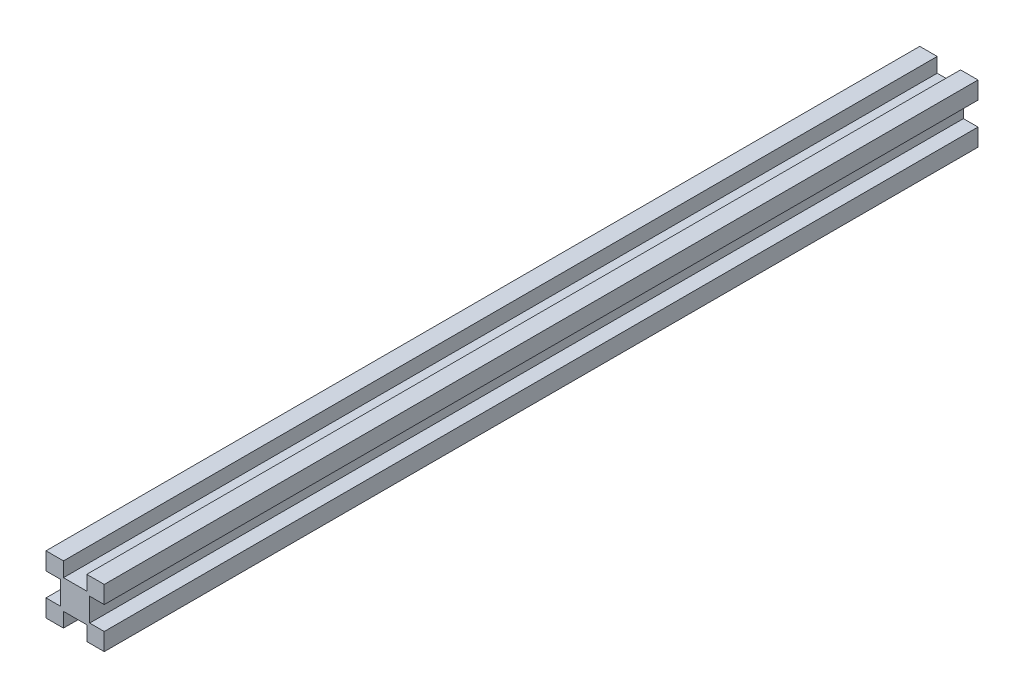
SolidWorks part; units mm, degrees
ref_plane "Alzado" through (0, 0, 0) normal (0, 0, 1) x (1, 0, 0)
ref_plane "Planta" through (0, 0, 0) normal (0, 1, 0) x (1, 0, 0)
ref_plane "Vista lateral" through (0, 0, 0) normal (1, 0, 0) x (0, 0, -1)
sketch "Croquis1" plane through (0, 0, 0) normal (0, 0, 1) x (1, 0, 0)
  line L1 (-23.5326, 14.5417) -> (-3.5326, 14.5417)
  line L2 (-23.5326, 14.5417) -> (-23.5326, -5.4583)
  line L3 (-23.5326, -5.4583) -> (-3.5326, -5.4583)
  line L4 (-3.5326, 14.5417) -> (-3.5326, -5.4583)
  line L5 (-23.5326, 14.5417) -> (-3.5326, -5.4583) construction
  line L6 (-23.5326, -5.4583) -> (-3.5326, 14.5417) construction
  point P0 (-13.5326, 4.5417)
  dimension "D1" = 20
extrude "Saliente-Extruir1" add sketch "Croquis1" along normal blind 300
sketch "Croquis2" plane through (0, 0, 300) normal (0, 0, 1) x (1, 0, 0)
  line L0 (-23.5326, 4.5417) -> (-3.5326, 4.5417) construction
  line L1 (-3.5326, 14.5417) -> (-23.5326, 14.5417) construction
  line L2 (-13.5326, 9.5417) -> (-17.5326, 9.5417)
  line L3 (-13.5326, 9.5417) -> (-9.5326, 9.5417)
  line L4 (-17.5326, 9.5417) -> (-17.5326, 14.5417)
  line L5 (-9.5326, 9.5417) -> (-9.5326, 14.5417)
  line L6 (-17.5326, 14.5417) -> (-9.5326, 14.5417)
  line L7 (-23.5326, 14.5417) -> (-23.5326, -5.4583) construction
  line L8 (-3.5326, -5.4583) -> (-3.5326, 14.5417) construction
  line L9 (-13.5326, 14.5417) -> (-13.5326, -5.4583) construction
  line L10 (-23.5326, -5.4583) -> (-3.5326, -5.4583) construction
  line L11 (-9.5326, -0.4583) -> (-9.5326, -5.4583)
  line L12 (-13.5326, -0.4583) -> (-9.5326, -0.4583)
  line L13 (-13.5326, -0.4583) -> (-17.5326, -0.4583)
  line L14 (-17.5326, -5.4583) -> (-9.5326, -5.4583)
  line L15 (-17.5326, -0.4583) -> (-17.5326, -5.4583)
  line L16 (-23.5326, 4.5417) -> (-23.5326, 8.5417)
  line L17 (-23.5326, 8.5417) -> (-18.5326, 8.5417)
  line L18 (-18.5326, 8.5417) -> (-18.5326, 0.5417)
  line L19 (-18.5326, 0.5417) -> (-23.5326, 0.5417)
  line L20 (-23.5326, 0.5417) -> (-23.5326, 4.5417)
  line L21 (-8.5326, 8.5417) -> (-8.5326, 0.5417)
  line L22 (-8.5326, 0.5417) -> (-3.5326, 0.5417)
  line L23 (-3.5326, 0.5417) -> (-3.5326, 4.5417)
  line L24 (-3.5326, 4.5417) -> (-3.5326, 8.5417)
  line L25 (-3.5326, 8.5417) -> (-8.5326, 8.5417)
  dimension "D1" = 4
  dimension "D2" = 5
extrude "Cortar-Extruir1" cut sketch "Croquis2" against normal blind 320
